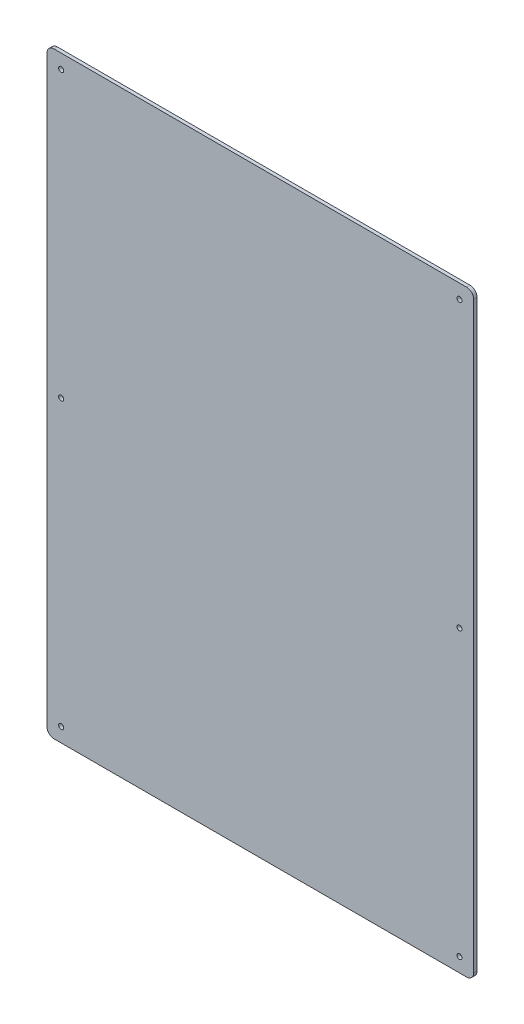
SolidWorks part; units mm, degrees
material "1023 Carbon Steel Sheet (SS)"
ref_plane "Front Plane" through (0, 0, 0) normal (0, 0, 1) x (1, 0, 0)
ref_plane "Top Plane" through (0, 0, 0) normal (0, 1, 0) x (1, 0, 0)
ref_plane "Right Plane" through (0, 0, 0) normal (1, 0, 0) x (0, 0, -1)
sketch "Sketch1" plane through (0, 0, 0) normal (0, 0, 1) x (1, 0, 0)
  line L1 (-8.937, 7.194) -> (372.063, 7.194)
  line L2 (-8.937, 7.194) -> (-8.937, -526.206)
  line L3 (-8.937, -526.206) -> (372.063, -526.206)
  line L4 (372.063, 7.194) -> (372.063, -526.206)
  dimension "D1" = 533.4
  dimension "D2" = 381
extrude "Boss-Extrude1" add sketch "Sketch1" along normal blind 3.048
fillet "Fillet1" radius 6.35 4 edges at (-8.937, -526.206, 1.524) (372.063, -526.206, 1.524) (372.063, 7.194, 1.524) (-8.937, 7.194, 1.524)
sketch "Sketch2" plane through (0, 0, 3.048) normal (0, 0, 1) x (1, 0, 0)
  line L0 (365.713, 7.194) -> (-2.587, 7.194) construction
  line L1 (3.763, -5.506) -> (359.363, -5.506)
  line L2 (3.763, -5.506) -> (3.763, -513.506)
  line L3 (3.763, -513.506) -> (359.363, -513.506)
  line L4 (359.363, -5.506) -> (359.363, -513.506)
  line L5 (372.063, -519.856) -> (372.063, 0.844) construction
  line L6 (-2.587, -526.206) -> (365.713, -526.206) construction
  point P8 (3.763, -259.506)
  point P9 (3.763, -5.506)
  point P10 (359.363, -259.506)
  point P11 (3.763, -513.506)
  point P12 (359.363, -513.506)
  point P14 (359.363, -5.506)
  dimension "D1" = 355.6
  dimension "D2" = 12.7
  dimension "D3" = 12.7
  dimension "D4" = 12.7
hole_wizard "#8 Clearance Slot1" positions "Sketch4" profile "Sketch3" size "#8" standard "ANSI Inch" slot yes
sketch "Sketch4" plane through (0, 0, 3.048) normal (0, 0, 1) x (1, 0, 0)
  point P0 (3.763, -5.506)
  point P3 (3.763, -259.506)
  point P6 (3.763, -513.506)
  point P9 (359.363, -513.506)
  point P12 (359.363, -259.506)
  point P15 (359.363, -5.506)
sketch "Sketch3" plane through (3.763, -5.506, 3.048) normal (1, 0, 0) x (0, -1, 0)
  line L0 (0, 0) -> (0, 11.0027)
  line L1 (0, 11.0027) -> (2.2479, 9.652)
  line L2 (2.2479, 9.652) -> (2.2479, 0)
  line L5 (2.2479, 0) -> (0, 0)
  line L10 (0, 11.0027) -> (-2.2479, 9.652) construction
  line L11 (0, -6.35) -> (0, 107.95) construction
  dimension "Hole Dia." = 4.4958
  dimension "Hole Depth" = 9.652
  dimension "Drill Angle" = 118
